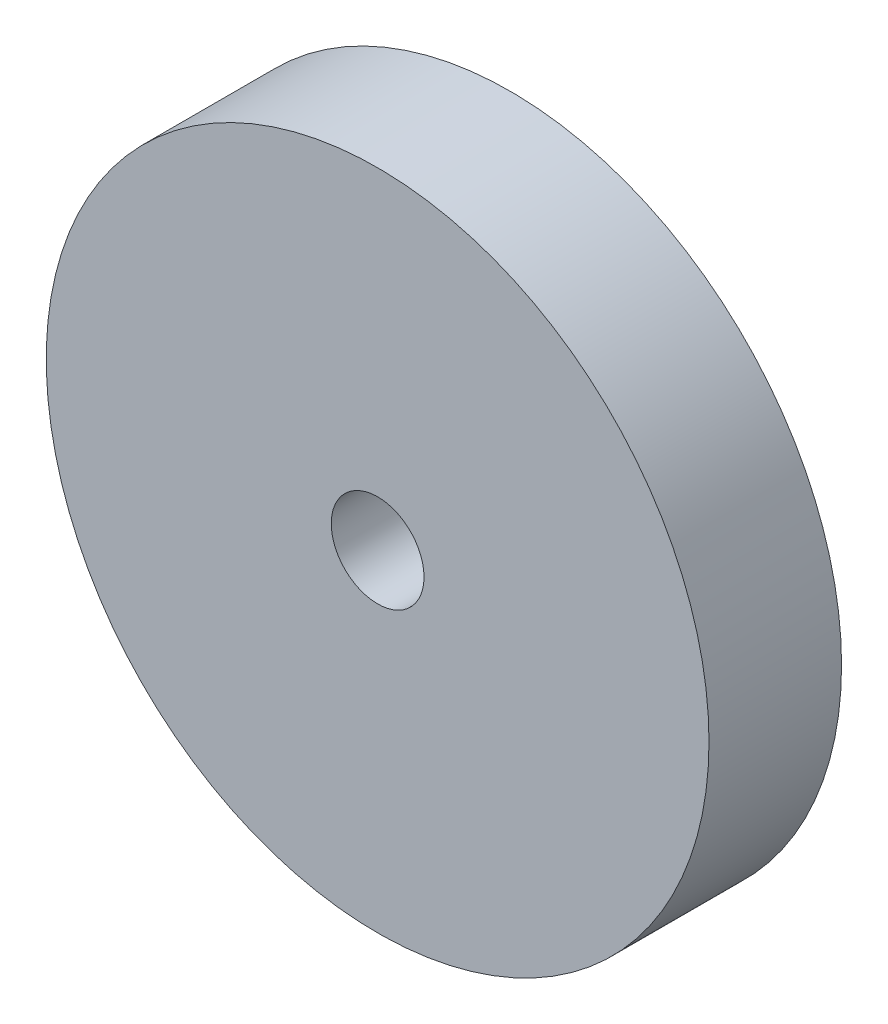
SolidWorks part; units mm, degrees
ref_plane "Front Plane" through (0, 0, 0) normal (0, 0, 1) x (1, 0, 0)
ref_plane "Top Plane" through (0, 0, 0) normal (0, 1, 0) x (1, 0, 0)
ref_plane "Right Plane" through (0, 0, 0) normal (1, 0, 0) x (0, 0, -1)
sketch "Sketch1" plane through (0, 0, 0) normal (0, 0, 1) x (1, 0, 0)
  circle A0 centre (0, 0) radius 2.5
  circle A1 centre (0, 0) radius 0.35
  dimension "D1" = 5
  dimension "D2" = 0.7
extrude "Boss-Extrude1" add sketch "Sketch1" along normal blind 1
